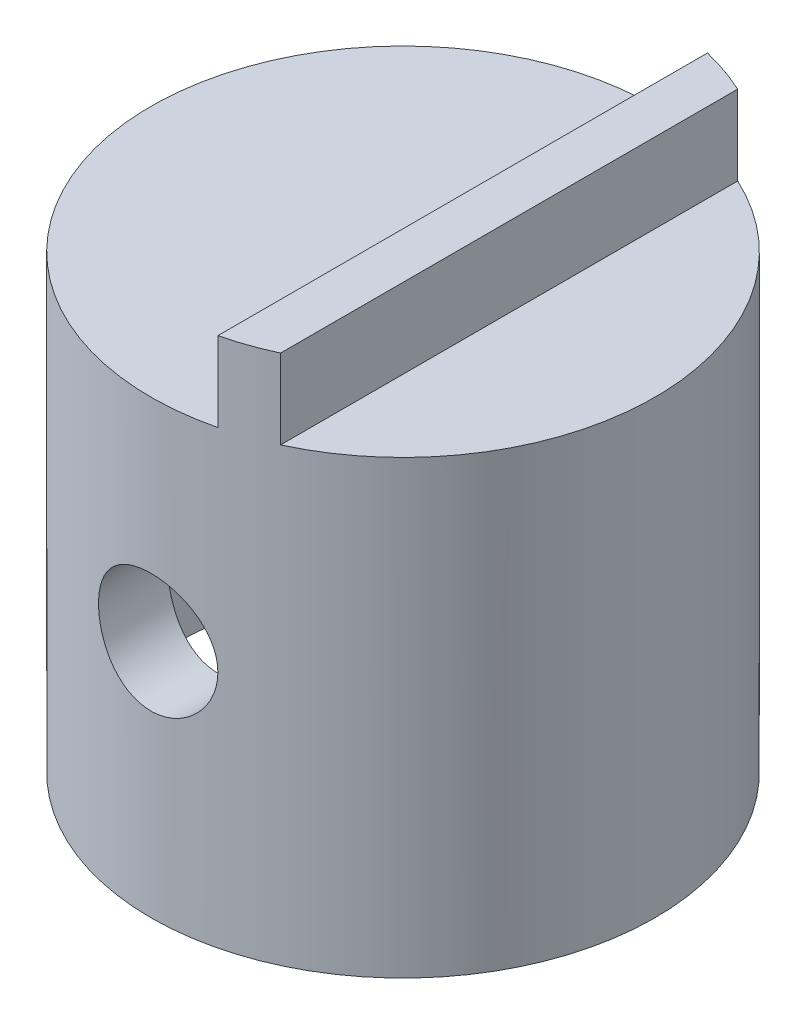
SolidWorks part; units mm, degrees
ref_plane "XZ (Face)" through (0, 0, 0) normal (0, 0, 1) x (1, 0, 0)
ref_plane "XY (Dessus)" through (0, 0, 0) normal (0, 1, 0) x (1, 0, 0)
ref_plane "YZ (Droite)" through (0, 0, 0) normal (1, 0, 0) x (0, 0, -1)
sketch "Esquisse1" plane through (0, 0, 0) normal (0, 1, 0) x (1, 0, 0)
  circle A0 centre (0, 0) radius 9.5
  dimension "D1" = 19
extrude "Base-Extrusion" add sketch "Esquisse1" along normal blind 17
sketch "Esquisse2" plane through (0, 17, 0) normal (0, 1, 0) x (-1, 0, 0)
  line L0 (-2.25, -9.2297) -> (-2.25, 9.2297)
  line L1 (-4, 8.6168) -> (-4, -8.6168)
  arc A0 (-4, -8.6168) -> (-2.25, -9.2297) centre (0, 0) ccw
  circle A1 centre (0, 0) radius 9.5
  arc A2 (-2.25, 9.2297) -> (-4, 8.6168) centre (0, 0) ccw
  dimension "D2" = 2.25
  dimension "D3" = 1.75
  dimension "D1" = 0
extrude "Boss.-Extru.1" add sketch "Esquisse2" along normal blind 3
sketch "Esquisse3" plane through (0, 0, 0) normal (0, 0, 1) x (1, 0, 0)
  line L0 (0, 0) -> (0, 21) construction
  line L1 (8.5, 0) -> (8.5, 5)
  line L2 (8.5, 5) -> (7, 5)
  line L3 (7, 5) -> (7, 12.5)
  line L4 (7, 12.5) -> (8.5, 12.5)
  line L5 (8.5, 12.5) -> (8.5, 15)
  line L6 (8.5, 15) -> (0, 15)
  line L7 (0, 15) -> (0, 0)
  line L8 (0, 0) -> (8.5, 0)
  line L9 (-9.5, 0) -> (9.5, 0) construction
  line L10 (7, 9) -> (-12, 9) construction
  dimension "D1" = 17
  dimension "D2" = 14
  dimension "D3" = 15
  dimension "D4" = 5
  dimension "D5" = 12.5
revolve "Enlèvement de matière-Révolution1" cut sketch "Esquisse3" angle 360 about L0
sketch "Esquisse4" plane through (0, 0, 0) normal (0, 0, 1) x (1, 0, 0)
  line L0 (0, 0) -> (0, 21) construction
  line L1 (7, 9) -> (-12, 9) construction
  circle A0 centre (0, 9) radius 2.25
  circle A1 centre (0, 9) radius 2.25 construction
  point P0 (0, 9)
extrude "Enlèv. mat.-Extru.1" cut sketch "Esquisse4" against normal through all and the other way through all
